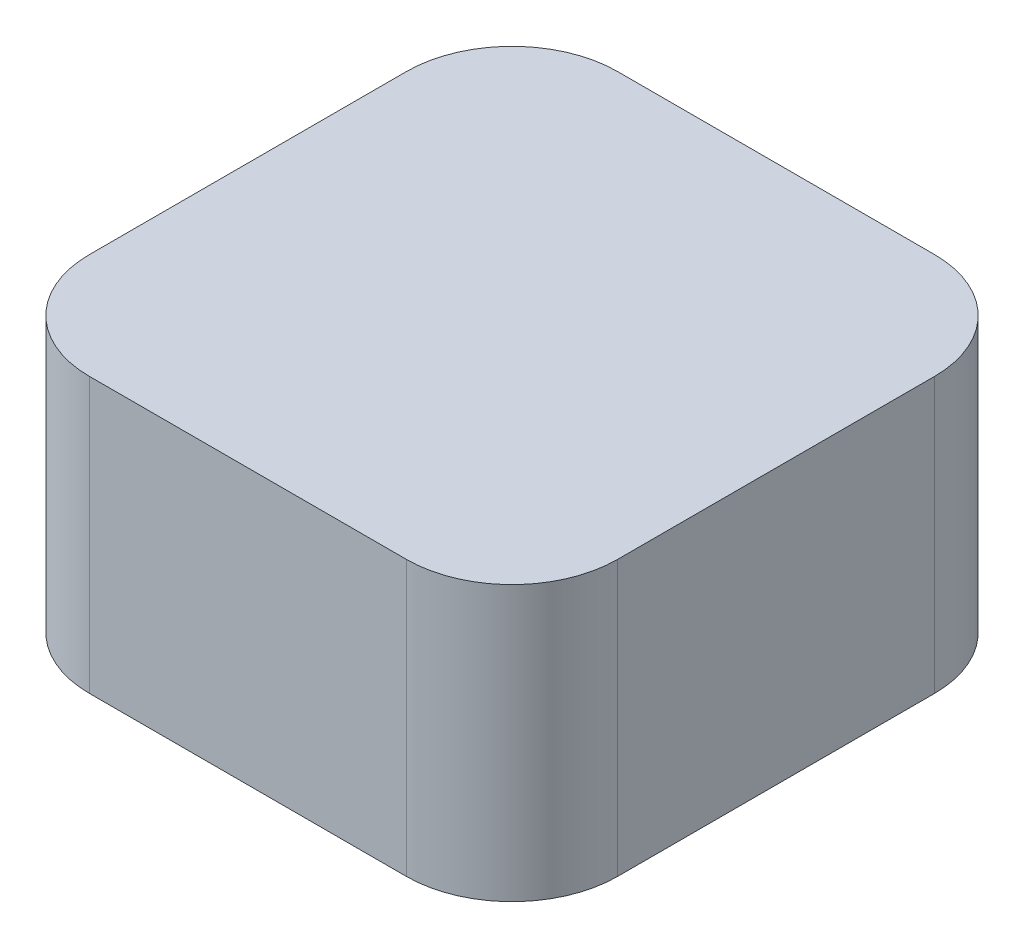
SolidWorks part; units mm, degrees
ref_plane "Front Plane" through (0, 0, 0) normal (0, 0, 1) x (1, 0, 0)
ref_plane "Top Plane" through (0, 0, 0) normal (0, 1, 0) x (1, 0, 0)
ref_plane "Right Plane" through (0, 0, 0) normal (1, 0, 0) x (0, 0, -1)
sketch "Sketch1" plane through (0, 0, 0) normal (0, 1, 0) x (1, 0, 0)
  line L1 (0, 0) -> (12.5, 0)
  line L2 (0, 0) -> (0, 12.5)
  line L3 (0, 12.5) -> (12.5, 12.5)
  line L4 (12.5, 0) -> (12.5, 12.5)
  dimension "D1" = 12.5
  dimension "D2" = 12.5
extrude "Boss-Extrude1" add sketch "Sketch1" along normal blind 6.5
fillet "Fillet1" radius 2.5 4 edges at (12.5, 3.25, -12.5) (0, 3.25, -12.5) (0, 3.25, 0) (12.5, 3.25, 0)
